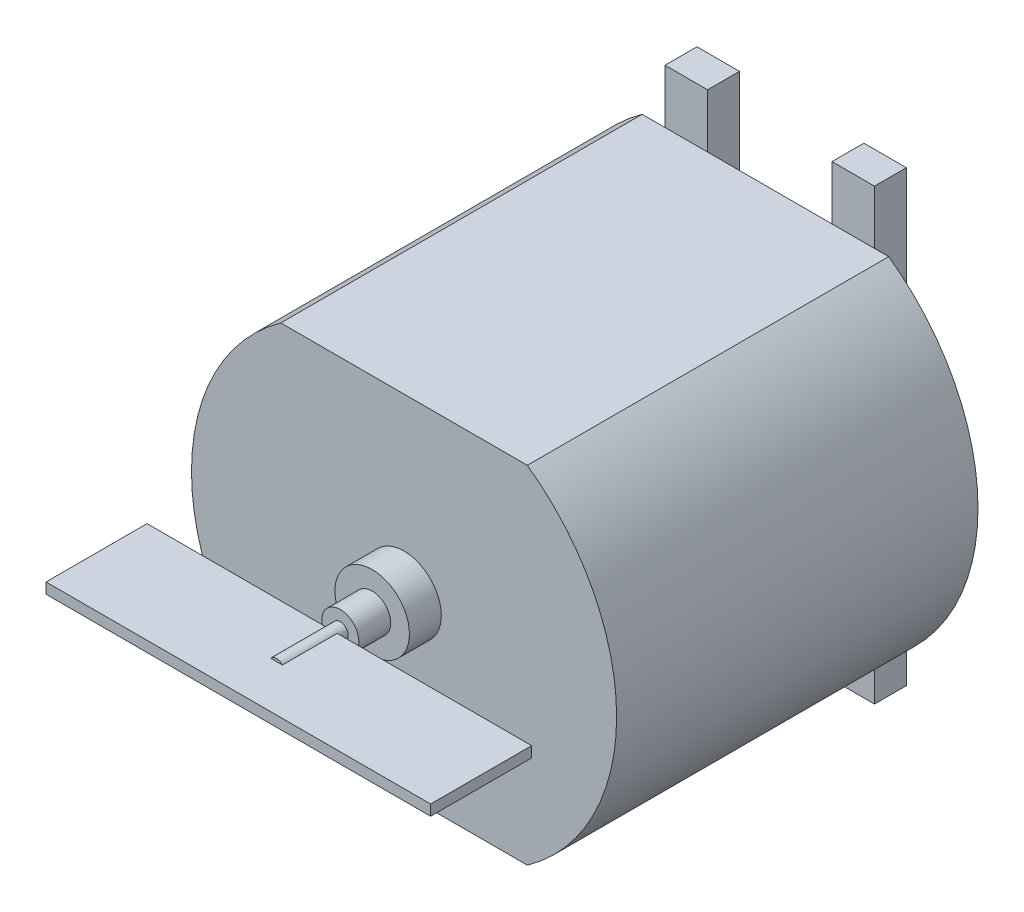
SolidWorks part; units mm, degrees
ref_plane "Front Plane" through (0, 0, 0) normal (0, 0, 1) x (1, 0, 0)
ref_plane "Top Plane" through (0, 0, 0) normal (0, 1, 0) x (1, 0, 0)
ref_plane "Right Plane" through (0, 0, 0) normal (1, 0, 0) x (0, 0, -1)
sketch "Sketch1" plane through (0, 0, 0) normal (0, 0, 1) x (1, 0, 0)
  line L0 (-11.5995, 16.2927) -> (11.5995, 16.2927)
  line L1 (-11.5995, -16.2927) -> (11.5995, -16.2927)
  arc A0 (-11.5995, 16.2927) -> (-11.5995, -16.2927) centre (0, 0) ccw
  arc A1 (11.5995, -16.2927) -> (11.5995, 16.2927) centre (0, 0) ccw
extrude "Boss-Extrude1" add sketch "Sketch1" along normal blind 34
sketch "Sketch2" plane through (0, 0, 34) normal (0, 0, 1) x (1, 0, 0)
  circle A0 centre (0, 0) radius 3.5037
extrude "Boss-Extrude2" add sketch "Sketch2" along normal blind 3
sketch "Sketch3" plane through (0, 0, 37) normal (0, 0, 1) x (1, 0, 0)
  circle A0 centre (0, 0) radius 1.7463
extrude "Boss-Extrude3" add sketch "Sketch3" along normal blind 3
sketch "Sketch4" plane through (0, 0, 40) normal (0, 0, 1) x (1, 0, 0)
  circle A0 centre (0, 0) radius 0.7493
extrude "Boss-Extrude4" add sketch "Sketch4" along normal blind 6
sketch "Sketch5" plane through (0, 0, 0) normal (0, 0, -1) x (-1, 0, 0)
  line L1 (-10.2611, 21.3699) -> (-6.2611, 21.3699)
  line L2 (-10.2611, 21.3699) -> (-10.2611, -20.8346)
  line L3 (-10.2611, -20.8346) -> (-6.2611, -20.8346)
  line L4 (-6.2611, 21.3699) -> (-6.2611, -20.8346)
  line L5 (5.4429, 21.3699) -> (9.4429, 21.3699)
  line L6 (5.4429, 21.3699) -> (5.4429, -20.8346)
  line L7 (5.4429, -20.8346) -> (9.4429, -20.8346)
  line L8 (9.4429, 21.3699) -> (9.4429, -20.8346)
extrude "Boss-Extrude5" add sketch "Sketch5" along normal blind 3
sketch "Sketch6" plane through (0, 0, 34) normal (0, 0, 1) x (1, 0, 0)
  line L1 (-9.4429, 21.3699) -> (-5.4429, 21.3699)
  line L2 (-9.4429, 21.3699) -> (-9.4429, -20.8346)
  line L3 (-9.4429, -20.8346) -> (-5.4429, -20.8346)
  line L4 (-5.4429, 21.3699) -> (-5.4429, -20.8346)
  line L5 (6.2611, 21.3699) -> (10.2611, 21.3699)
  line L6 (6.2611, 21.3699) -> (6.2611, -20.8346)
  line L7 (6.2611, -20.8346) -> (10.2611, -20.8346)
  line L8 (10.2611, 21.3699) -> (10.2611, -20.8346)
extrude "Boss-Extrude6" [suppressed] add sketch "Sketch6" along normal blind 2
sketch "Sketch7" plane through (0, 0, 0) normal (0, 1, 0) x (1, 0, 0)
  line L1 (-17.3315, -50.3569) -> (18.8552, -50.3569)
  line L2 (-17.3315, -50.3569) -> (-17.3315, -40.8503)
  line L3 (-17.3315, -40.8503) -> (18.8552, -40.8503)
  line L4 (18.8552, -50.3569) -> (18.8552, -40.8503)
extrude "Boss-Extrude7" add sketch "Sketch7" along normal blind 0.5 and the other way blind 0.5
